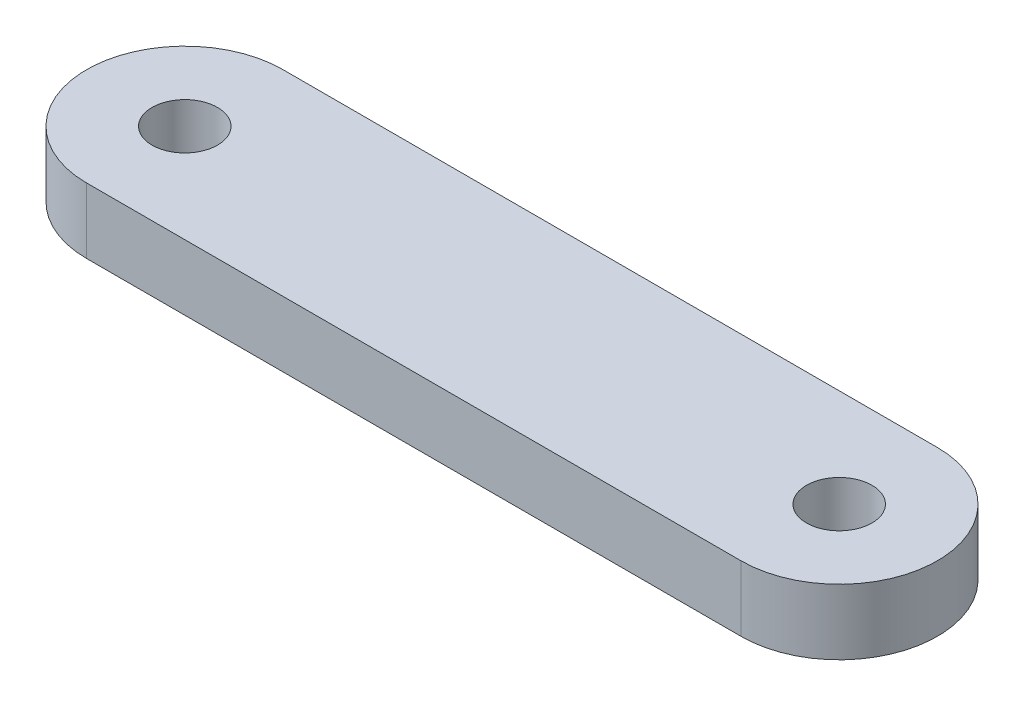
SolidWorks part; units mm, degrees
ref_plane "Plano frontal" through (0, 0, 0) normal (0, 0, 1) x (1, 0, 0)
ref_plane "Plano superior" through (0, 0, 0) normal (0, 1, 0) x (1, 0, 0)
ref_plane "Plano direito" through (0, 0, 0) normal (1, 0, 0) x (0, 0, -1)
sketch "Esboço3" plane through (0, 0, 0) normal (0, 1, 0) x (1, 0, 0)
  line L2 (-50, 15) -> (50, 15)
  line L3 (-50, -15) -> (50, -15)
  arc A0 (50, 15) -> (50, -15) centre (50, 0) cw
  arc A1 (-50, 15) -> (-50, -15) centre (-50, 0) ccw
  point P4 (0, 0)
  dimension "D2" = 30
  dimension "D4" = 15
  dimension "D1" = 100
  dimension "D3" = 100
  dimension "D5" = 50
extrude "Ressalto-extrusão2" add sketch "Esboço3" along normal blind 10
sketch "Esboço4" plane through (0, 10, 0) normal (0, 1, 0) x (1, 0, 0)
  line L0 (-65, 0) -> (65, 0) construction
  line L1 (0, 15) -> (0, -15) construction
  line L2 (50, 15) -> (-50, 15) construction
  line L3 (-50, -15) -> (50, -15) construction
  arc A0 (-50, 15) -> (-50, -15) centre (-50, 0) ccw construction
  arc A1 (50, -15) -> (50, 15) centre (50, 0) ccw construction
  circle A2 centre (-50, 0) radius 5
  circle A3 centre (50, 0) radius 5
extrude "Corte-extrusão1" cut sketch "Esboço4" against normal blind 10
